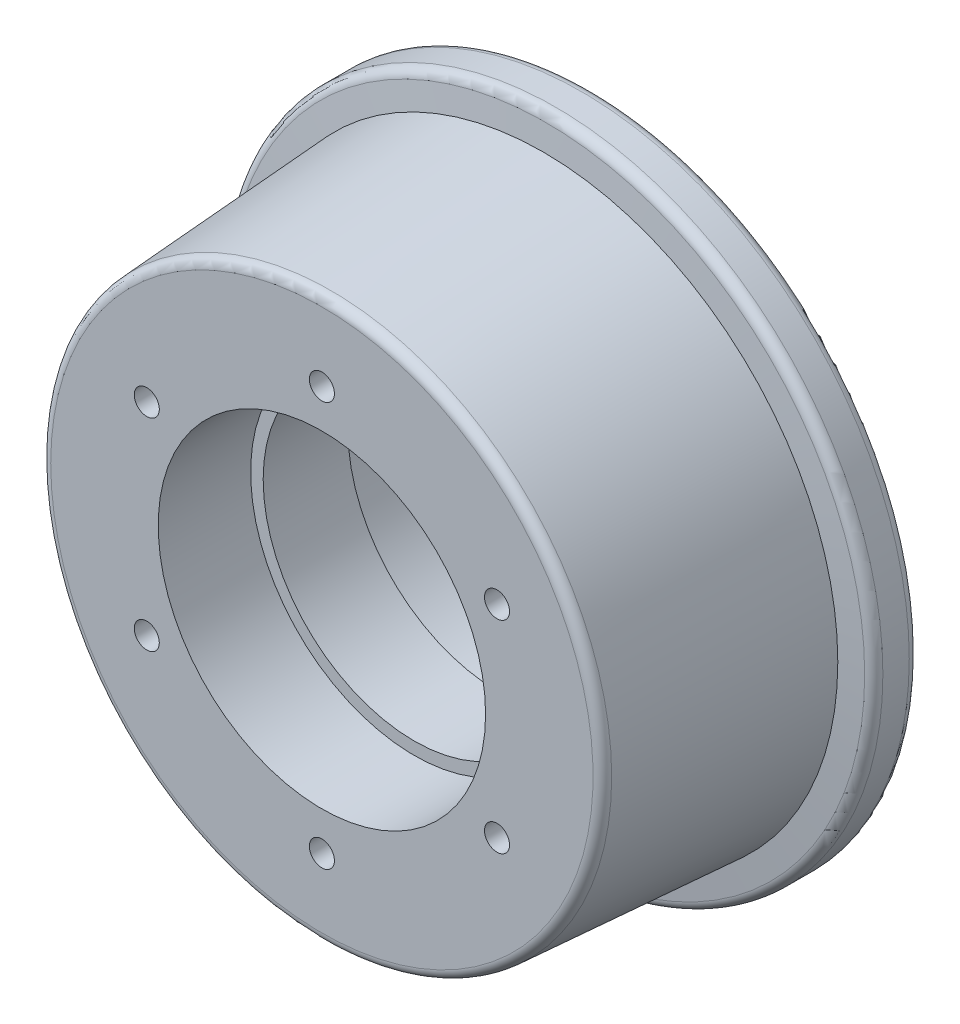
SolidWorks part; units mm, degrees
ref_plane "前视基准面" through (0, 0, 0) normal (0, 0, 1) x (1, 0, 0)
ref_plane "上视基准面" through (0, 0, 0) normal (0, 1, 0) x (1, 0, 0)
ref_plane "右视基准面" through (0, 0, 0) normal (1, 0, 0) x (0, 0, -1)
sketch "草图1" plane through (0, 0, 0) normal (1, 0, 0) x (0, 0, -1)
  line L0 (-1000, 0) -> (49000, 0) construction
  line L1 (0, 0) -> (0, 150) construction
  line L2 (-22, 78.5) -> (22, 78.5)
  line L3 (22, 78.5) -> (22, 85)
  line L4 (22, 85) -> (75, 85)
  line L5 (-22, 78.5) -> (-22, 85)
  line L6 (-22, 85) -> (-70, 85)
  line L7 (-70, 85) -> (-70, 145.5)
  line L8 (75, 85) -> (75, 140)
  line L9 (75, 140) -> (70, 140)
  line L10 (70, 140) -> (70, 170)
  line L11 (-70, 145.5) -> (45, 152.8929)
  line L12 (45, 152.8929) -> (46.798, 170)
  line L13 (46.798, 170) -> (70, 170)
  dimension "D2" = 150
  dimension "D3" = 78.5
  dimension "D4" = 85
  dimension "D5" = 85
  dimension "D6" = 48
  dimension "D7" = 145
  dimension "D8" = 145.5
  dimension "D9" = 140
  dimension "D10" = 5
  dimension "D11" = 170
  dimension "D12" = 22
  dimension "D13" = 22
  dimension "D14" = 25
  dimension "D15" = 96
revolve "旋转1" add sketch "草图1" angle 360 about L0
fillet "圆角2" radius 5 3 edges at (170, 0, -46.798) (170, 0, -70) (145.5, 0, 70)
sketch "草图2" plane through (0, 0, 70) normal (0, 0, 1) x (1, 0, 0)
  line L0 (0, -1000) -> (0, 49000) construction
  circle A0 centre (0, 105) radius 6.5
  dimension "D1" = 13
  dimension "D2" = 105
extrude "切除-拉伸1" cut sketch "草图2" against normal blind 25
pattern_circular "阵列(圆周)1" count 6 over 360 about axis through (0, 0, 0) along (0, 0, 1) of "切除-拉伸1"
sketch "草图3" plane through (0, 0, -75) normal (0, 0, -1) x (-1, 0, 0)
  line L0 (0, -1000) -> (0, 49000) construction
  circle A0 centre (0, 115) radius 8
  dimension "D1" = 16
  dimension "D2" = 115
extrude "切除-拉伸2" cut sketch "草图3" against normal blind 35
pattern_circular "阵列(圆周)2" count 6 over 360 about axis through (0, 0, 0) along (0, 0, 1) of "切除-拉伸2"
